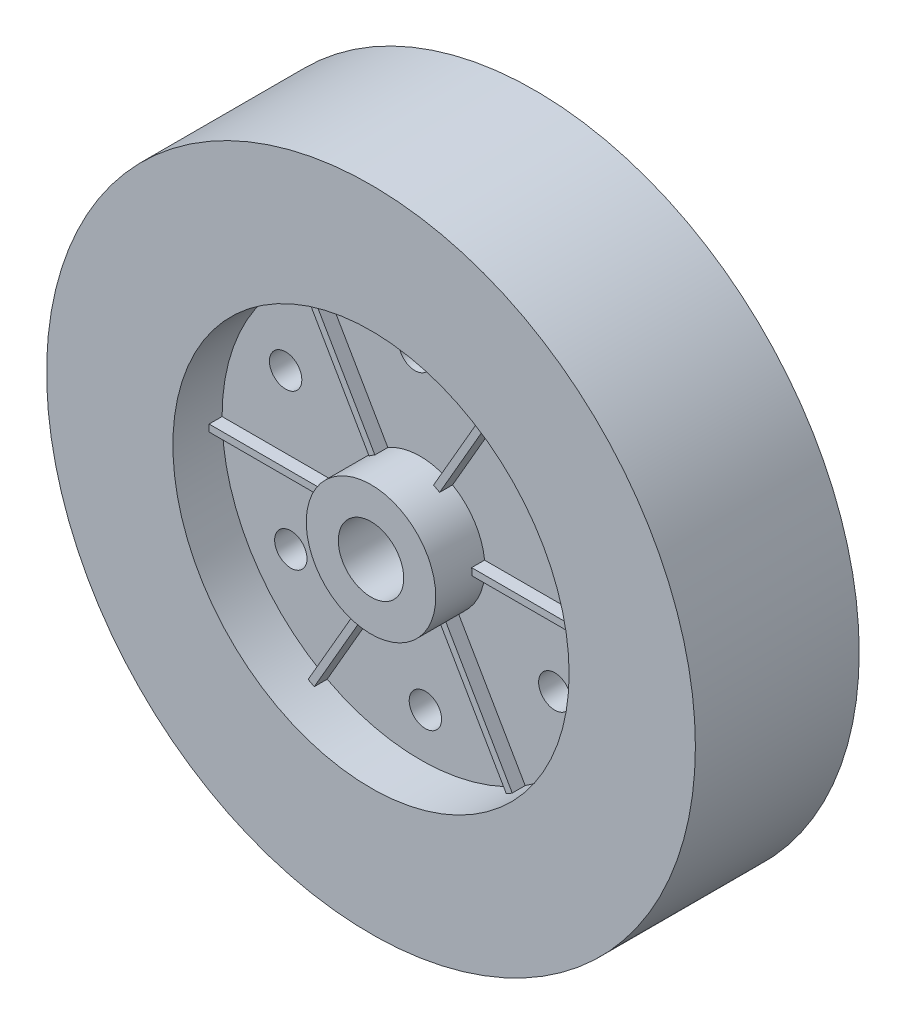
SolidWorks part; units mm, degrees
ref_plane "Front Plane" through (0, 0, 0) normal (0, 0, 1) x (1, 0, 0)
ref_plane "Top Plane" through (0, 0, 0) normal (0, 1, 0) x (1, 0, 0)
ref_plane "Right Plane" through (0, 0, 0) normal (1, 0, 0) x (0, 0, -1)
sketch "Sketch1" plane through (0, 0, 0) normal (0, 0, 1) x (1, 0, 0)
  circle A0 centre (0, 0) radius 50.1
  dimension "D1" = 100.2
extrude "Boss-Extrude5" add sketch "Sketch1" along normal blind 25.3
sketch "Sketch4" plane through (0, 0, 25.3) normal (0, 0, 1) x (1, 0, 0)
  circle A0 centre (0, 0) radius 30.6
  dimension "D1" = 61.2
extrude "Cut-Extrude1" cut sketch "Sketch4" against normal blind 7.6 contours A0
sketch "Sketch5" plane through (0, 0, 0) normal (0, 0, -1) x (-1, 0, 0)
  circle A0 centre (0, 0) radius 30.6
  dimension "D1" = 61.2
extrude "Cut-Extrude2" cut sketch "Sketch5" against normal blind 7.6
sketch "Sketch6" plane through (0, 0, 17.7) normal (0, 0, 1) x (1, 0, 0)
  circle A0 centre (0, 0) radius 10
  circle A1 centre (0, 0) radius 5.05
  dimension "D1" = 20
  dimension "D2" = 10.1
extrude "Boss-Extrude7" add sketch "Sketch6" along normal blind 7.6 contours A0
sketch "Sketch7" plane through (0, 0, 25.3) normal (0, 0, 1) x (1, 0, 0)
  circle A0 centre (0, 0) radius 5.05
  dimension "D1" = 10.1
extrude "Cut-Extrude5" cut sketch "Sketch7" against normal blind 10000 contours A0
sketch "Sketch8" plane through (0, 0, 17.7) normal (0, 0, 1) x (1, 0, 0)
  line L0 (-30.6, 0) -> (-10, 0)
  line L1 (10, 0) -> (30.6, 0)
  line L2 (-10, 0) -> (-14.6722, 0)
  line L3 (-30.5814, -1.0668) -> (-9.9429, -1.0668)
  line L4 (9.9429, -1.0668) -> (30.5814, -1.0668)
  line L5 (-16.2146, 25.9509) -> (-5.8953, 8.0774)
  line L6 (-15.3, 26.5004) -> (-5, 8.6603)
  line L7 (14.3668, 27.0177) -> (4.0476, 9.1442)
  line L8 (15.3, 26.5004) -> (5, 8.6603)
  line L9 (30.5814, 1.0668) -> (9.9429, 1.0668)
  line L10 (30.6, 0) -> (10, 0)
  line L11 (16.2146, -25.9509) -> (5.8953, -8.0774)
  line L12 (15.3, -26.5004) -> (5, -8.6603)
  line L13 (-14.3668, -27.0177) -> (-4.0476, -9.1442)
  line L14 (-15.3, -26.5004) -> (-5, -8.6603)
  circle A0 centre (0, 0) radius 30.6 construction
  circle A1 centre (0, 0) radius 30.6 construction
  circle A2 centre (0, 0) radius 10 construction
  circle A3 centre (0, 0) radius 10 construction
  arc A4 (-9.9429, -1.0668) -> (-10, 0) centre (0, 0) cw
  arc A5 (-30.5814, -1.0668) -> (-30.6, 0) centre (0, 0) cw
  arc A6 (-5.8953, 8.0774) -> (-5, 8.6603) centre (0, 0) cw
  arc A7 (-16.2146, 25.9509) -> (-15.3, 26.5004) centre (0, 0) cw
  arc A8 (4.0476, 9.1442) -> (5, 8.6603) centre (0, 0) cw
  arc A9 (14.3668, 27.0177) -> (15.3, 26.5004) centre (0, 0) cw
  arc A10 (9.9429, 1.0668) -> (10, 0) centre (0, 0) cw
  arc A11 (30.5814, 1.0668) -> (30.6, 0) centre (0, 0) cw
  arc A12 (5.8953, -8.0774) -> (5, -8.6603) centre (0, 0) cw
  arc A13 (16.2146, -25.9509) -> (15.3, -26.5004) centre (0, 0) cw
  arc A14 (-4.0476, -9.1442) -> (-5, -8.6603) centre (0, 0) cw
  arc A15 (-14.3668, -27.0177) -> (-15.3, -26.5004) centre (0, 0) cw
  point P22 (0, 0)
  point P43 (0, 0)
  dimension "D1" = 6
extrude "Boss-Extrude8" add sketch "Sketch8" along normal blind 2 contours L6 A6 L5 A7 | L7 A8 L8 A9 | L9 A10 L10 A11 | L0 A5 L3 A4 | L14 A14 L13 A15 | L11 A12 L12 A13
sketch "Sketch9" plane through (0, 0, 7.6) normal (0, 0, 1) x (1, 0, 0)
  circle A0 centre (-19.9822, -12.4624) radius 2.5
  circle A1 centre (-20.7838, 11.0739) radius 2.5
  circle A2 centre (-0.8016, 23.5363) radius 2.5
  circle A3 centre (19.9822, 12.4624) radius 2.5
  circle A4 centre (20.7838, -11.0739) radius 2.5
  circle A5 centre (0.8016, -23.5363) radius 2.5
  point P2 (0, 0)
  point P15 (0, 0)
  dimension "D1" = 5
  dimension "D2" = 6
extrude "Cut-Extrude11" cut sketch "Sketch9" along normal through all
